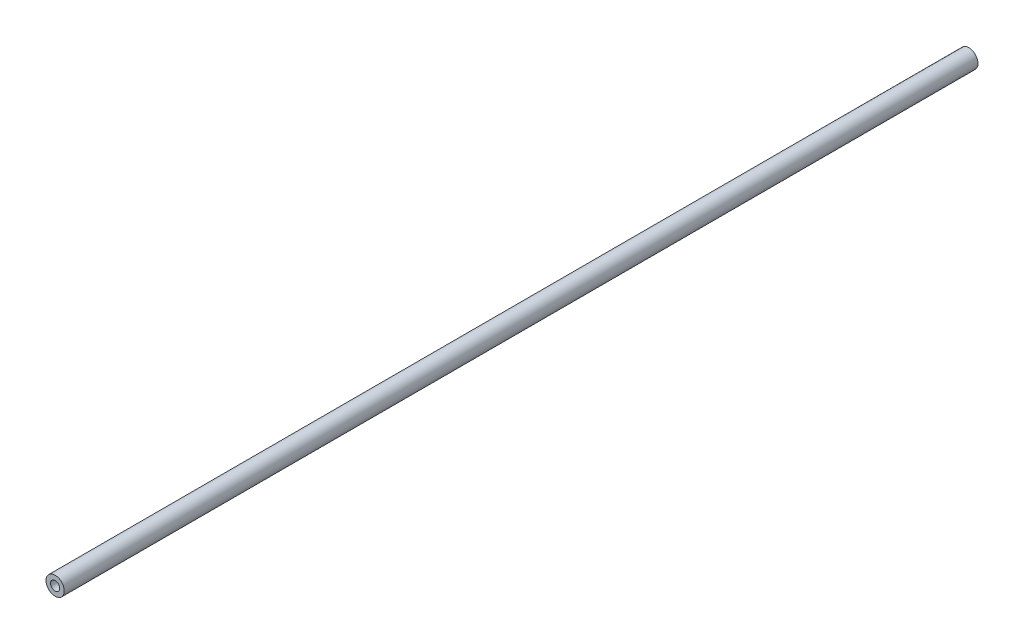
SolidWorks part; units mm, degrees
ref_plane "Ebene vorne" through (0, 0, 0) normal (0, 0, 1) x (1, 0, 0)
ref_plane "Ebene oben" through (0, 0, 0) normal (0, 1, 0) x (1, 0, 0)
ref_plane "Ebene rechts" through (0, 0, 0) normal (1, 0, 0) x (0, 0, -1)
sketch "Skizze1" plane through (0, 0, 0) normal (0, 0, 1) x (1, 0, 0)
  circle A0 centre (0, 0) radius 1
  circle A1 centre (0, 0) radius 2
  dimension "D1" = 4
  dimension "D2" = 2
extrude "Aufsatz-Linear austragen1" add sketch "Skizze1" along normal blind 200
